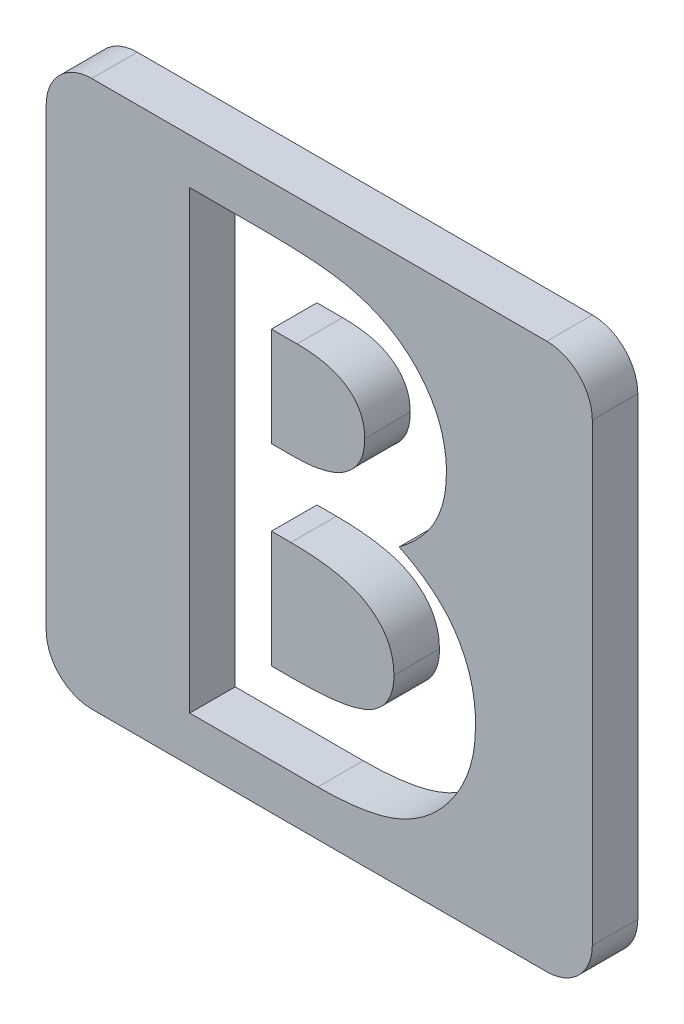
SolidWorks part; units mm, degrees
ref_plane "Front Plane" through (0, 0, 0) normal (0, 0, 1) x (1, 0, 0)
ref_plane "Top Plane" through (0, 0, 0) normal (0, 1, 0) x (1, 0, 0)
ref_plane "Right Plane" through (0, 0, 0) normal (1, 0, 0) x (0, 0, -1)
sketch "Sketch1" plane through (0, 0, 0) normal (0, 0, 1) x (1, 0, 0)
  line L1 (-50, 60) -> (50, 60)
  line L2 (-60, 50) -> (-60, -50)
  line L3 (-50, -60) -> (50, -60)
  line L4 (60, 50) -> (60, -50)
  line L5 (-60, 60) -> (60, -60) construction
  line L6 (-60, -60) -> (60, 60) construction
  arc A0 (-60, -50) -> (-50, -60) centre (-50, -50) ccw
  arc A1 (50, -60) -> (60, -50) centre (50, -50) ccw
  arc A2 (50, 60) -> (60, 50) centre (50, 50) cw
  arc A3 (-50, 60) -> (-60, 50) centre (-50, 50) ccw
  point P0 (0, 0)
  dimension "D3" = 10
  dimension "D1" = 120
  dimension "D2" = 120
extrude "Boss-Extrude1" add sketch "Sketch1" along normal blind 10 contours A3 L2 A0 L3 A1 L4 A2 L1
sketch "Sketch2" plane through (0, 0, 10) normal (0, 0, 1) x (1, 0, 0)
  line L0 (0, 0) -> (0, 40) construction
  line L1 (-50, 50) -> (50, 50) construction
  line L2 (-50, 50) -> (-50, -50) construction
  line L3 (-50, -50) -> (50, -50) construction
  line L4 (50, 50) -> (50, -50) construction
  line L5 (-50, 50) -> (50, -50) construction
  line L6 (-50, -50) -> (50, 50) construction
  line L7 (0, 40) -> (-40, 40) construction
  line L8 (-40, 40) -> (-40, 0) construction
  line L9 (-40, 0) -> (0, 0) construction
  line L11 (0, 20) -> (-20, 20) construction
  line L12 (-20, 40) -> (-20, 20) construction
  circle A0 centre (0, 40) radius 4 construction
  circle A1 centre (0, 20) radius 4 construction
  circle A2 centre (0, 0) radius 4 construction
  circle A3 centre (-20, 20) radius 4 construction
  circle A4 centre (-20, 40) radius 4 construction
  circle A5 centre (-40, 40) radius 4 construction
  circle A6 centre (0, 0) radius 4 construction
  circle A7 centre (20, 0) radius 4 construction
  circle A8 centre (40, 0) radius 4 construction
  circle A9 centre (40, 20) radius 4 construction
  circle A10 centre (40, 40) radius 4 construction
  circle A11 centre (20, 20) radius 4 construction
  circle A12 centre (0, 0) radius 4 construction
  circle A13 centre (0, -20) radius 4 construction
  circle A14 centre (0, -40) radius 4 construction
  circle A15 centre (20, -40) radius 4 construction
  circle A16 centre (40, -40) radius 4 construction
  circle A17 centre (20, -20) radius 4 construction
  circle A18 centre (0, 0) radius 4 construction
  circle A19 centre (-20, 0) radius 4 construction
  circle A20 centre (-40, 0) radius 4 construction
  circle A21 centre (-40, -20) radius 4 construction
  circle A22 centre (-40, -40) radius 4 construction
  circle A23 centre (-20, -20) radius 4 construction
  text T0 "B" font "Century Gothic" height 100
  point P0 (0, 0)
  point P55 (0, 0)
  dimension "D4" = 8
  dimension "D1" = 100
  dimension "D2" = 100
  dimension "D3" = 40
  dimension "D5" = 4
extrude "Cut-Extrude15" cut sketch "Sketch2" against normal blind 10
